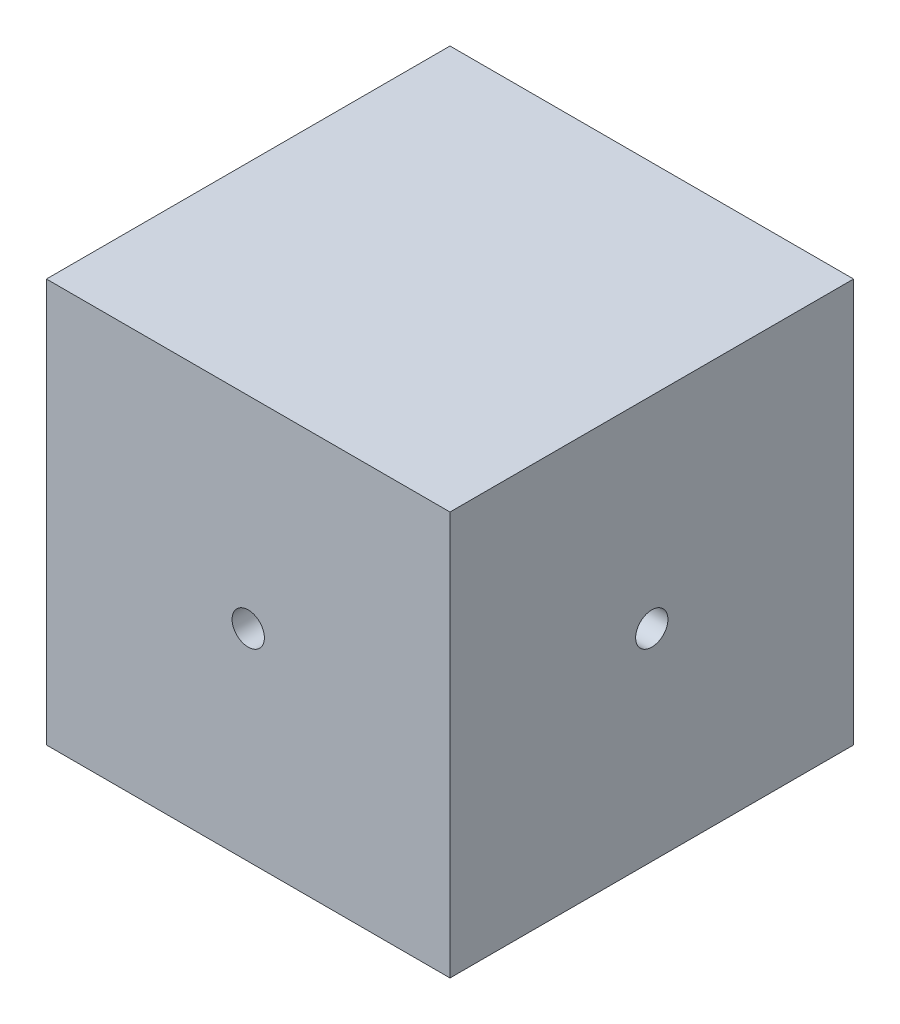
SolidWorks part; units mm, degrees
ref_plane "Plano frontal" through (0, 0, 0) normal (0, 0, 1) x (1, 0, 0)
ref_plane "Plano superior" through (0, 0, 0) normal (0, 1, 0) x (1, 0, 0)
ref_plane "Plano direito" through (0, 0, 0) normal (1, 0, 0) x (0, 0, -1)
sketch "Esboço5" plane through (0, 0, 0) normal (0, 0, 1) x (1, 0, 0)
  line L1 (-25, 25) -> (25, 25)
  line L2 (-25, 25) -> (-25, -25)
  line L3 (-25, -25) -> (25, -25)
  line L4 (25, 25) -> (25, -25)
  line L5 (-25, 25) -> (25, -25) construction
  line L6 (-25, -25) -> (25, 25) construction
  point P0 (0, 0)
  dimension "D1" = 50
  dimension "D2" = 50
extrude "Ressalto-extrusão2" add sketch "Esboço5" along normal blind 50
sketch "Esboço6" plane through (0, 0, 50) normal (0, 0, 1) x (1, 0, 0)
  circle A0 centre (0, 0) radius 2
  dimension "D1" = 4
extrude "Corte-extrusão1" cut sketch "Esboço6" against normal blind 50
sketch "Esboço7" plane through (25, 0, 0) normal (1, 0, 0) x (0, 0, -1)
  line L0 (-25, 25) -> (-25, -25) construction
  line L1 (-50, 25) -> (0, 25) construction
  line L2 (-50, -25) -> (0, -25) construction
  circle A0 centre (-25, 0) radius 2
  dimension "D1" = 4
extrude "Corte-extrusão2" cut sketch "Esboço7" against normal blind 50
